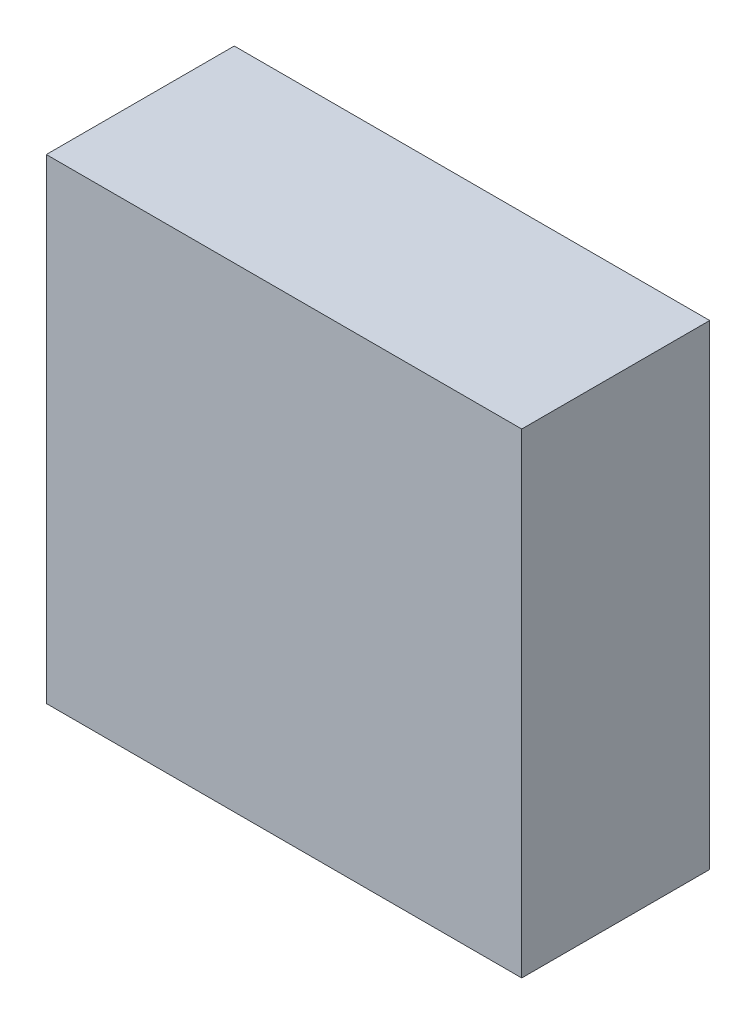
SolidWorks part; units mm, degrees
ref_plane "Plano frontal" through (0, 0, 0) normal (0, 0, 1) x (1, 0, 0)
ref_plane "Plano superior" through (0, 0, 0) normal (0, 1, 0) x (1, 0, 0)
ref_plane "Plano direito" through (0, 0, 0) normal (1, 0, 0) x (0, 0, -1)
sketch "Esboço1" plane through (0, 0, 0) normal (0, 0, 1) x (1, 0, 0)
  line L1 (21.5, -21.5) -> (-21.5, -21.5)
  line L2 (21.5, -21.5) -> (21.5, 21.5)
  line L3 (21.5, 21.5) -> (-21.5, 21.5)
  line L4 (-21.5, -21.5) -> (-21.5, 21.5)
  line L5 (21.5, -21.5) -> (-21.5, 21.5) construction
  line L6 (21.5, 21.5) -> (-21.5, -21.5) construction
  point P0 (0, 0)
  dimension "D1" = 43
  dimension "D2" = 43
extrude "Ressalto-extrusão1" add sketch "Esboço1" against normal blind 17
